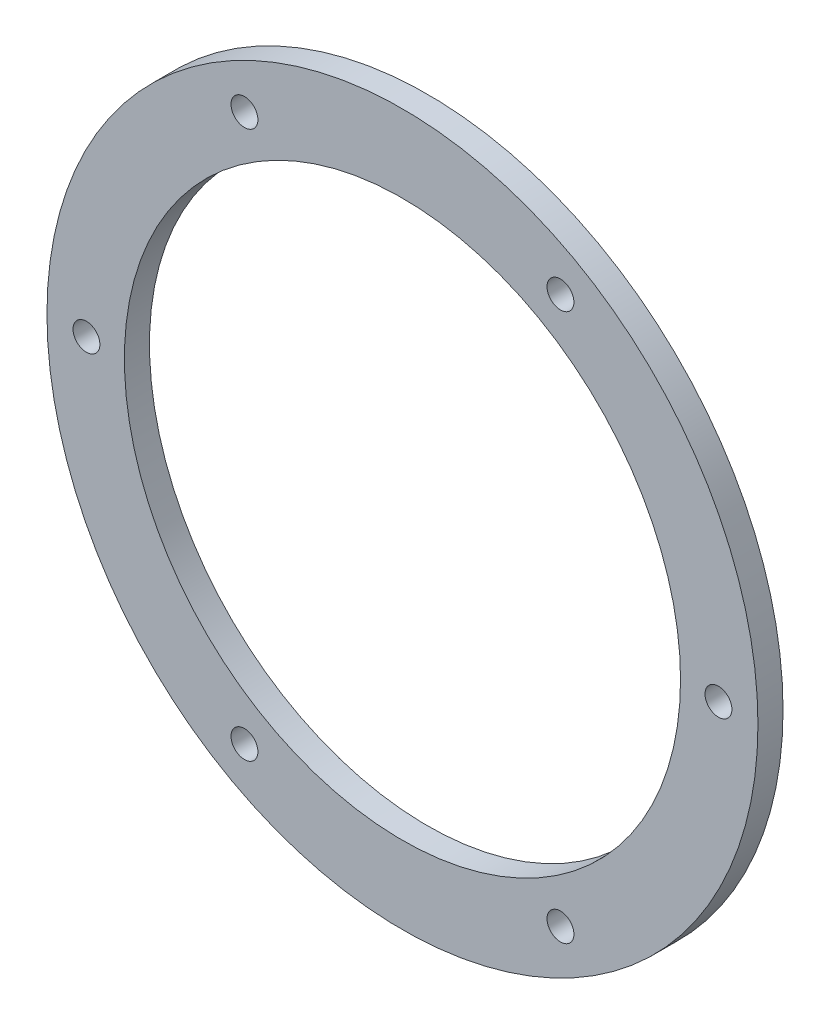
SolidWorks part; units mm, degrees
material "Aleación 6061"
ref_plane "Alzado" through (0, 0, 0) normal (0, 0, 1) x (1, 0, 0)
ref_plane "Planta" through (0, 0, 0) normal (0, 1, 0) x (1, 0, 0)
ref_plane "Vista lateral" through (0, 0, 0) normal (1, 0, 0) x (0, 0, -1)
sketch "Croquis1" plane through (0, 0, 0) normal (0, 0, 1) x (1, 0, 0)
  circle A0 centre (0, 0) radius 45
  circle A1 centre (0, 0) radius 35.2
  dimension "D1" = 90
  dimension "D2" = 70.4
extrude "Aro" add sketch "Croquis1" along normal blind 3.175 from offset 69.85
sketch "Croquis2" plane through (0, 0, 0) normal (0, 0, 1) x (1, 0, 0)
  circle A0 centre (40, 0) radius 1.7
  circle A1 centre (20, 34.641) radius 1.7
  circle A2 centre (-20, 34.641) radius 1.7
  circle A3 centre (-40, 0) radius 1.7
  circle A4 centre (-20, -34.641) radius 1.7
  circle A5 centre (20, -34.641) radius 1.7
  dimension "D1" = 3.4
  dimension "D2" = 3.4
  dimension "D3" = 3.4
  dimension "D4" = 3.4
  dimension "D5" = 3.4
  dimension "D6" = 3.4
  dimension "D7" = 40
  dimension "D8" = 20
  dimension "D9" = 34.641
  dimension "D10" = 20
  dimension "D11" = 34.641
  dimension "D12" = 40
  dimension "D13" = 20
  dimension "D14" = 34.641
  dimension "D15" = 20
  dimension "D16" = 34.641
extrude "Barrenos_M3" cut sketch "Croquis2" along normal blind 3.175 from offset 69.85
